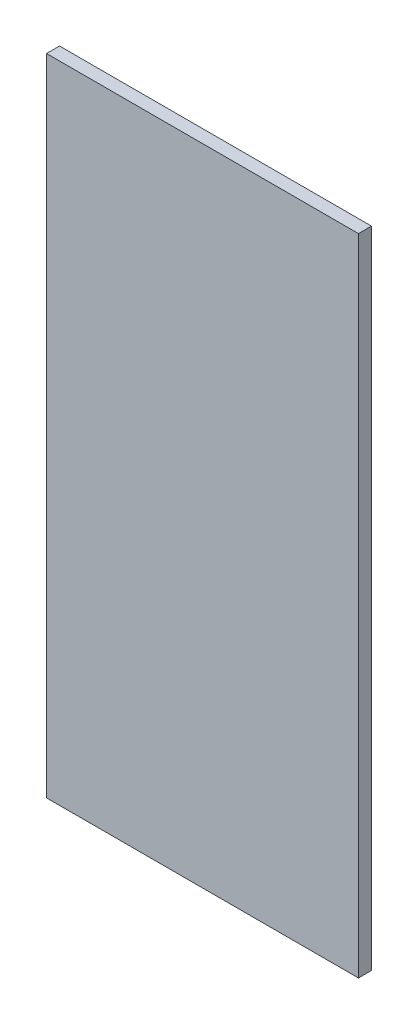
SolidWorks part; units mm, degrees
material "6061 Alloy"
ref_plane "Front Plane" through (0, 0, 0) normal (0, 0, 1) x (1, 0, 0)
ref_plane "Top Plane" through (0, 0, 0) normal (0, 1, 0) x (1, 0, 0)
ref_plane "Right Plane" through (0, 0, 0) normal (1, 0, 0) x (0, 0, -1)
sketch "Sketch1" plane through (0, 0, 0) normal (0, 0, 1) x (1, 0, 0)
  line L1 (-76.2, 157.48) -> (76.2, 157.48)
  line L2 (-76.2, 157.48) -> (-76.2, -157.48)
  line L3 (-76.2, -157.48) -> (76.2, -157.48)
  line L4 (76.2, 157.48) -> (76.2, -157.48)
  line L5 (-76.2, 157.48) -> (76.2, -157.48) construction
  line L6 (-76.2, -157.48) -> (76.2, 157.48) construction
  point P0 (0, 0)
  dimension "D1" = 314.96
  dimension "D2" = 152.4
extrude "Boss-Extrude1" add sketch "Sketch1" along normal blind 6.35
